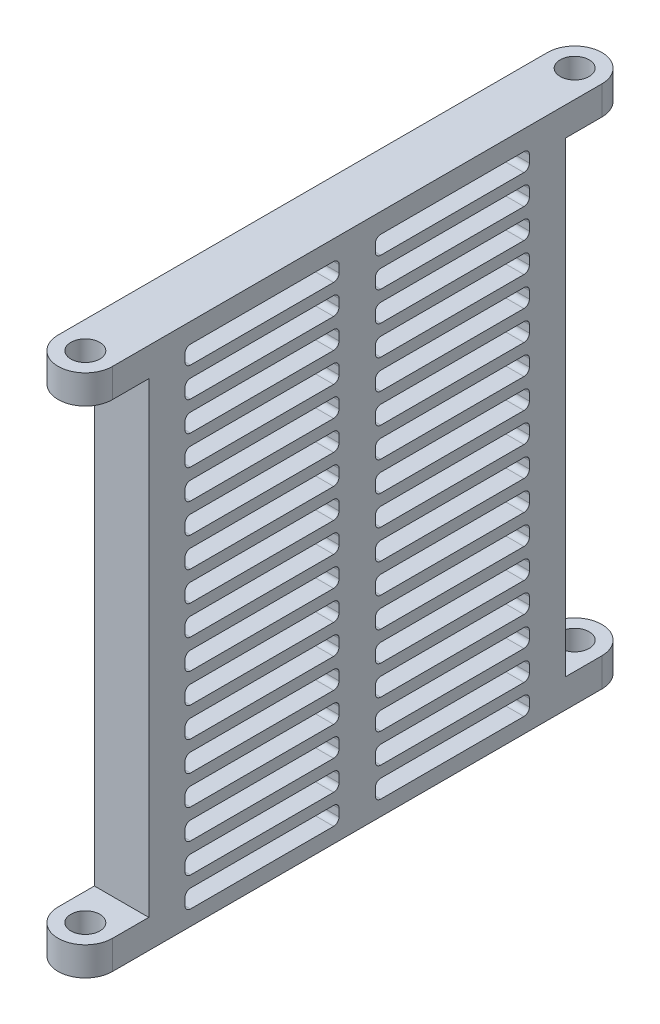
SolidWorks part; units mm, degrees
ref_plane "Front Plane" through (0, 0, 0) normal (0, 0, 1) x (1, 0, 0)
ref_plane "Top Plane" through (0, 0, 0) normal (0, 1, 0) x (1, 0, 0)
ref_plane "Right Plane" through (0, 0, 0) normal (1, 0, 0) x (0, 0, -1)
sketch "Sketch2" plane through (0, 0, 0) normal (0, 1, 0) x (1, 0, 0)
  line L0 (-3, 0) -> (-3, -54)
  line L1 (3, -54) -> (3, 0)
  arc A0 (3, 0) -> (-3, 0) centre (0, 0) ccw
  arc A1 (-3, -54) -> (3, -54) centre (0, -54) ccw
  circle A2 centre (0, 0) radius 1.6
  circle A3 centre (0, -54) radius 1.6
  dimension "D1" = 3.2
  dimension "D2" = 3
  dimension "D3" = 54
extrude "Boss-Extrude1" add sketch "Sketch2" along normal blind 3.175
sketch "Sketch3" plane through (0, 3.175, 0) normal (0, 1, 0) x (1, 0, 0)
  line L0 (-3, 0) -> (-3, -54) construction
  line L1 (-3, -4) -> (3, -4)
  line L2 (-3, -4) -> (-3, -50)
  line L3 (-3, -50) -> (3, -50)
  line L4 (3, -4) -> (3, -50)
  line L5 (3, -54) -> (3, 0) construction
  circle A0 centre (0, -54) radius 1.6 construction
  point P9 (0, -50)
  dimension "D1" = 4
  dimension "D2" = 4
extrude "Boss-Extrude2" add sketch "Sketch3" along normal blind 51.48
ref_plane "Plane1" through (0, 28.915, 0) normal (0, 1, 0) x (1, 0, 0)
mirror "Mirror2" about plane through (0, 28.915, 0) normal (0, 1, 0) of "Boss-Extrude1"
sketch "Sketch4" plane through (3, 0, 0) normal (1, 0, 0) x (0, 0, -1)
  line L0 (-4, 54.655) -> (-50, 54.655) construction
  line L1 (-8.6, 13.4236) -> (-24.4, 13.4236)
  line L2 (-8, 12.8236) -> (-8, 12.0236)
  line L3 (-4, 3.175) -> (-50, 3.175) construction
  line L4 (-8.6, 11.4236) -> (-24.4, 11.4236)
  line L5 (-25, 12.8236) -> (-25, 12.0236)
  line L11 (-27, 57.83) -> (-27, 0) construction
  line L12 (-54, 57.83) -> (0, 57.83) construction
  line L24 (-54, 0) -> (0, 0) construction
  line L25 (-4, 54.655) -> (-4, 3.175) construction
  line L30 (-8.6, 55.655) -> (-24.4, 55.655)
  line L39 (-8, 55.055) -> (-8, 54.255)
  line L40 (-8.6, 53.655) -> (-24.4, 53.655)
  line L41 (-25, 55.055) -> (-25, 54.255)
  line L46 (-8, 55.655) -> (-25, 53.655) construction
  line L47 (-8, 53.655) -> (-25, 55.655) construction
  line L64 (-8.6, 52.4064) -> (-24.4, 52.4064)
  line L69 (-8, 51.8064) -> (-8, 51.0064)
  line L70 (-8.6, 50.4064) -> (-24.4, 50.4064)
  line L71 (-25, 51.8064) -> (-25, 51.0064)
  line L72 (-4, 51.4064) -> (-50, 51.4064) construction
  line L73 (-8, 52.4064) -> (-25, 50.4064) construction
  line L74 (-8, 50.4064) -> (-25, 52.4064) construction
  line L75 (-8.6, 49.1579) -> (-24.4, 49.1579)
  line L76 (-8, 48.5579) -> (-8, 47.7579)
  line L77 (-8.6, 47.1579) -> (-24.4, 47.1579)
  line L78 (-25, 48.5579) -> (-25, 47.7579)
  line L79 (-4, 48.1579) -> (-50, 48.1579) construction
  line L132 (-8, 49.1579) -> (-25, 47.1579) construction
  line L133 (-8, 47.1579) -> (-25, 49.1579) construction
  line L134 (-8.6, 45.9093) -> (-24.4, 45.9093)
  line L135 (-8, 45.3093) -> (-8, 44.5093)
  line L136 (-8.6, 43.9093) -> (-24.4, 43.9093)
  line L137 (-25, 45.3093) -> (-25, 44.5093)
  line L138 (-4, 44.9093) -> (-50, 44.9093) construction
  line L139 (-8, 45.9093) -> (-25, 43.9093) construction
  line L140 (-8, 43.9093) -> (-25, 45.9093) construction
  line L141 (-8.6, 42.6607) -> (-24.4, 42.6607)
  line L142 (-8, 42.0607) -> (-8, 41.2607)
  line L143 (-8.6, 40.6607) -> (-24.4, 40.6607)
  line L144 (-25, 42.0607) -> (-25, 41.2607)
  line L145 (-4, 41.6607) -> (-50, 41.6607) construction
  line L146 (-8, 42.6607) -> (-25, 40.6607) construction
  line L147 (-8, 40.6607) -> (-25, 42.6607) construction
  line L148 (-8.6, 39.4121) -> (-24.4, 39.4121)
  line L149 (-8, 38.8121) -> (-8, 38.0121)
  line L186 (-4, 12.4236) -> (-50, 12.4236) construction
  line L187 (-8, 13.4236) -> (-25, 11.4236) construction
  line L188 (-8, 11.4236) -> (-25, 13.4236) construction
  line L189 (-8.6, 10.175) -> (-24.4, 10.175)
  line L190 (-8, 9.575) -> (-8, 8.775)
  line L191 (-8.6, 8.175) -> (-24.4, 8.175)
  line L192 (-25, 9.575) -> (-25, 8.775)
  line L193 (-4, 9.175) -> (-50, 9.175) construction
  line L194 (-8, 10.175) -> (-25, 8.175) construction
  line L195 (-8, 8.175) -> (-25, 10.175) construction
  line L196 (-46, 1.6779) -> (-29, 3.6779) construction
  line L197 (-46, 3.6779) -> (-29, 1.6779) construction
  line L198 (-46, 4.9264) -> (-29, 6.9264) construction
  line L199 (-46, 6.9264) -> (-29, 4.9264) construction
  line L200 (-46, 14.6721) -> (-29, 16.6721) construction
  line L201 (-8.6, 37.4121) -> (-24.4, 37.4121)
  line L202 (-25, 38.8121) -> (-25, 38.0121)
  line L203 (-4, 38.4121) -> (-50, 38.4121) construction
  line L204 (-8, 39.4121) -> (-25, 37.4121) construction
  line L205 (-8, 37.4121) -> (-25, 39.4121) construction
  line L206 (-8.6, 36.1636) -> (-24.4, 36.1636)
  line L207 (-8, 35.5636) -> (-8, 34.7636)
  line L208 (-8.6, 34.1636) -> (-24.4, 34.1636)
  line L209 (-25, 35.5636) -> (-25, 34.7636)
  line L210 (-4, 35.1636) -> (-50, 35.1636) construction
  line L211 (-8, 36.1636) -> (-25, 34.1636) construction
  line L212 (-8, 34.1636) -> (-25, 36.1636) construction
  line L213 (-8.6, 32.915) -> (-24.4, 32.915)
  line L214 (-8, 32.315) -> (-8, 31.515)
  line L215 (-8.6, 30.915) -> (-24.4, 30.915)
  line L216 (-25, 32.315) -> (-25, 31.515)
  line L217 (-4, 31.915) -> (-50, 31.915) construction
  line L218 (-8, 32.915) -> (-25, 30.915) construction
  line L219 (-8, 30.915) -> (-25, 32.915) construction
  line L220 (-8.6, 29.6664) -> (-24.4, 29.6664)
  line L221 (-8, 29.0664) -> (-8, 28.2664)
  line L222 (-8.6, 27.6664) -> (-24.4, 27.6664)
  line L223 (-25, 29.0664) -> (-25, 28.2664)
  line L224 (-4, 28.6664) -> (-50, 28.6664) construction
  line L225 (-8, 29.6664) -> (-25, 27.6664) construction
  line L226 (-8, 27.6664) -> (-25, 29.6664) construction
  line L227 (-8.6, 26.4179) -> (-24.4, 26.4179)
  line L228 (-8, 25.8179) -> (-8, 25.0179)
  line L229 (-8.6, 24.4179) -> (-24.4, 24.4179)
  line L230 (-25, 25.8179) -> (-25, 25.0179)
  line L231 (-4, 25.4179) -> (-50, 25.4179) construction
  line L232 (-8, 26.4179) -> (-25, 24.4179) construction
  line L233 (-8, 24.4179) -> (-25, 26.4179) construction
  line L234 (-8.6, 23.1693) -> (-24.4, 23.1693)
  line L235 (-8, 22.5693) -> (-8, 21.7693)
  line L236 (-8.6, 21.1693) -> (-24.4, 21.1693)
  line L237 (-25, 22.5693) -> (-25, 21.7693)
  line L238 (-4, 22.1693) -> (-50, 22.1693) construction
  line L239 (-8, 23.1693) -> (-25, 21.1693) construction
  line L240 (-8, 21.1693) -> (-25, 23.1693) construction
  line L241 (-8.6, 19.9207) -> (-24.4, 19.9207)
  line L242 (-8, 19.3207) -> (-8, 18.5207)
  line L243 (-8.6, 17.9207) -> (-24.4, 17.9207)
  line L244 (-25, 19.3207) -> (-25, 18.5207)
  line L245 (-4, 18.9207) -> (-50, 18.9207) construction
  line L246 (-8, 19.9207) -> (-25, 17.9207) construction
  line L247 (-8, 17.9207) -> (-25, 19.9207) construction
  line L248 (-8.6, 16.6721) -> (-24.4, 16.6721)
  line L249 (-8, 16.0721) -> (-8, 15.2721)
  line L250 (-8.6, 14.6721) -> (-24.4, 14.6721)
  line L251 (-25, 16.0721) -> (-25, 15.2721)
  line L252 (-4, 15.6721) -> (-50, 15.6721) construction
  line L253 (-8, 16.6721) -> (-25, 14.6721) construction
  line L254 (-8, 14.6721) -> (-25, 16.6721) construction
  line L255 (-46, 16.6721) -> (-29, 14.6721) construction
  line L256 (-46, 17.9207) -> (-29, 19.9207) construction
  line L257 (-46, 19.9207) -> (-29, 17.9207) construction
  line L258 (-46, 21.1693) -> (-29, 23.1693) construction
  line L259 (-46, 23.1693) -> (-29, 21.1693) construction
  line L260 (-46, 24.4179) -> (-29, 26.4179) construction
  line L261 (-46, 26.4179) -> (-29, 24.4179) construction
  line L262 (-46, 27.6664) -> (-29, 29.6664) construction
  line L263 (-46, 29.6664) -> (-29, 27.6664) construction
  line L264 (-46, 30.915) -> (-29, 32.915) construction
  line L265 (-46, 32.915) -> (-29, 30.915) construction
  line L266 (-46, 34.1636) -> (-29, 36.1636) construction
  line L267 (-46, 36.1636) -> (-29, 34.1636) construction
  line L268 (-46, 37.4121) -> (-29, 39.4121) construction
  line L269 (-46, 39.4121) -> (-29, 37.4121) construction
  line L270 (-46, 8.175) -> (-29, 10.175) construction
  line L271 (-46, 10.175) -> (-29, 8.175) construction
  line L272 (-46, 11.4236) -> (-29, 13.4236) construction
  line L273 (-46, 13.4236) -> (-29, 11.4236) construction
  line L274 (-46, 40.6607) -> (-29, 42.6607) construction
  line L275 (-46, 42.6607) -> (-29, 40.6607) construction
  line L276 (-46, 43.9093) -> (-29, 45.9093) construction
  line L277 (-46, 45.9093) -> (-29, 43.9093) construction
  line L278 (-46, 47.1579) -> (-29, 49.1579) construction
  line L279 (-46, 49.1579) -> (-29, 47.1579) construction
  line L392 (-8.6, 6.9264) -> (-24.4, 6.9264)
  line L393 (-8, 6.3264) -> (-8, 5.5264)
  line L394 (-8.6, 4.9264) -> (-24.4, 4.9264)
  line L395 (-25, 6.3264) -> (-25, 5.5264)
  line L396 (-4, 5.9264) -> (-50, 5.9264) construction
  line L397 (-8, 6.9264) -> (-25, 4.9264) construction
  line L398 (-8, 4.9264) -> (-25, 6.9264) construction
  line L399 (-8.6, 3.6779) -> (-24.4, 3.6779)
  line L400 (-8, 3.0779) -> (-8, 2.2779)
  line L401 (-8.6, 1.6779) -> (-24.4, 1.6779)
  line L402 (-25, 3.0779) -> (-25, 2.2779)
  line L403 (-4, 2.6779) -> (-50, 2.6779) construction
  line L404 (-8, 3.6779) -> (-25, 1.6779) construction
  line L405 (-8, 1.6779) -> (-25, 3.6779) construction
  line L406 (-46, 50.4064) -> (-29, 52.4064) construction
  line L407 (-46, 52.4064) -> (-29, 50.4064) construction
  line L408 (-46, 53.655) -> (-29, 55.655) construction
  line L409 (-46, 55.655) -> (-29, 53.655) construction
  line L410 (-29, 3.0779) -> (-29, 2.2779)
  line L411 (-45.4, 1.6779) -> (-29.6, 1.6779)
  line L412 (-46, 3.0779) -> (-46, 2.2779)
  line L413 (-45.4, 3.6779) -> (-29.6, 3.6779)
  line L414 (-29, 6.3264) -> (-29, 5.5264)
  line L415 (-45.4, 4.9264) -> (-29.6, 4.9264)
  line L416 (-46, 6.3264) -> (-46, 5.5264)
  line L417 (-45.4, 6.9264) -> (-29.6, 6.9264)
  line L418 (-29, 16.0721) -> (-29, 15.2721)
  line L419 (-45.4, 14.6721) -> (-29.6, 14.6721)
  line L420 (-46, 16.0721) -> (-46, 15.2721)
  line L421 (-45.4, 16.6721) -> (-29.6, 16.6721)
  line L422 (-29, 19.3207) -> (-29, 18.5207)
  line L423 (-45.4, 17.9207) -> (-29.6, 17.9207)
  line L424 (-46, 19.3207) -> (-46, 18.5207)
  line L425 (-45.4, 19.9207) -> (-29.6, 19.9207)
  line L426 (-29, 22.5693) -> (-29, 21.7693)
  line L427 (-45.4, 21.1693) -> (-29.6, 21.1693)
  line L428 (-46, 22.5693) -> (-46, 21.7693)
  line L429 (-45.4, 23.1693) -> (-29.6, 23.1693)
  line L430 (-29, 25.8179) -> (-29, 25.0179)
  line L431 (-45.4, 24.4179) -> (-29.6, 24.4179)
  line L432 (-46, 25.8179) -> (-46, 25.0179)
  line L433 (-45.4, 26.4179) -> (-29.6, 26.4179)
  line L434 (-29, 29.0664) -> (-29, 28.2664)
  line L435 (-45.4, 27.6664) -> (-29.6, 27.6664)
  line L436 (-46, 29.0664) -> (-46, 28.2664)
  line L437 (-45.4, 29.6664) -> (-29.6, 29.6664)
  line L438 (-29, 32.315) -> (-29, 31.515)
  line L439 (-45.4, 30.915) -> (-29.6, 30.915)
  line L440 (-46, 32.315) -> (-46, 31.515)
  line L441 (-45.4, 32.915) -> (-29.6, 32.915)
  line L442 (-29, 35.5636) -> (-29, 34.7636)
  line L443 (-45.4, 34.1636) -> (-29.6, 34.1636)
  line L444 (-46, 35.5636) -> (-46, 34.7636)
  line L445 (-45.4, 36.1636) -> (-29.6, 36.1636)
  line L446 (-29, 38.8121) -> (-29, 38.0121)
  line L447 (-45.4, 37.4121) -> (-29.6, 37.4121)
  line L448 (-29, 9.575) -> (-29, 8.775)
  line L449 (-45.4, 8.175) -> (-29.6, 8.175)
  line L450 (-46, 9.575) -> (-46, 8.775)
  line L451 (-45.4, 10.175) -> (-29.6, 10.175)
  line L452 (-46, 38.8121) -> (-46, 38.0121)
  line L453 (-45.4, 39.4121) -> (-29.6, 39.4121)
  line L454 (-29, 42.0607) -> (-29, 41.2607)
  line L455 (-45.4, 40.6607) -> (-29.6, 40.6607)
  line L456 (-46, 42.0607) -> (-46, 41.2607)
  line L457 (-45.4, 42.6607) -> (-29.6, 42.6607)
  line L458 (-29, 45.3093) -> (-29, 44.5093)
  line L459 (-45.4, 43.9093) -> (-29.6, 43.9093)
  line L460 (-46, 45.3093) -> (-46, 44.5093)
  line L461 (-45.4, 45.9093) -> (-29.6, 45.9093)
  line L462 (-29, 48.5579) -> (-29, 47.7579)
  line L463 (-45.4, 47.1579) -> (-29.6, 47.1579)
  line L464 (-46, 48.5579) -> (-46, 47.7579)
  line L465 (-45.4, 49.1579) -> (-29.6, 49.1579)
  line L466 (-29, 51.8064) -> (-29, 51.0064)
  line L467 (-45.4, 50.4064) -> (-29.6, 50.4064)
  line L468 (-46, 51.8064) -> (-46, 51.0064)
  line L469 (-45.4, 52.4064) -> (-29.6, 52.4064)
  line L470 (-29, 55.055) -> (-29, 54.255)
  line L471 (-45.4, 53.655) -> (-29.6, 53.655)
  line L472 (-46, 55.055) -> (-46, 54.255)
  line L473 (-45.4, 55.655) -> (-29.6, 55.655)
  line L474 (-29, 12.8236) -> (-29, 12.0236)
  line L475 (-45.4, 11.4236) -> (-29.6, 11.4236)
  line L476 (-46, 12.8236) -> (-46, 12.0236)
  line L477 (-45.4, 13.4236) -> (-29.6, 13.4236)
  arc A72 (-24.4, 13.4236) -> (-25, 12.8236) centre (-24.4, 12.8236) ccw
  arc A73 (-24.4, 11.4236) -> (-25, 12.0236) centre (-24.4, 12.0236) cw
  arc A74 (-8.6, 13.4236) -> (-8, 12.8236) centre (-8.6, 12.8236) cw
  arc A75 (-8, 12.0236) -> (-8.6, 11.4236) centre (-8.6, 12.0236) cw
  arc A76 (-24.4, 55.655) -> (-25, 55.055) centre (-24.4, 55.055) ccw
  arc A77 (-24.4, 53.655) -> (-25, 54.255) centre (-24.4, 54.255) cw
  arc A78 (-8.6, 55.655) -> (-8, 55.055) centre (-8.6, 55.055) cw
  arc A79 (-8, 54.255) -> (-8.6, 53.655) centre (-8.6, 54.255) cw
  arc A80 (-24.4, 52.4064) -> (-25, 51.8064) centre (-24.4, 51.8064) ccw
  arc A81 (-24.4, 50.4064) -> (-25, 51.0064) centre (-24.4, 51.0064) cw
  arc A82 (-8.6, 52.4064) -> (-8, 51.8064) centre (-8.6, 51.8064) cw
  arc A83 (-8, 51.0064) -> (-8.6, 50.4064) centre (-8.6, 51.0064) cw
  arc A84 (-24.4, 49.1579) -> (-25, 48.5579) centre (-24.4, 48.5579) ccw
  arc A85 (-24.4, 47.1579) -> (-25, 47.7579) centre (-24.4, 47.7579) cw
  arc A86 (-8.6, 49.1579) -> (-8, 48.5579) centre (-8.6, 48.5579) cw
  arc A87 (-8, 47.7579) -> (-8.6, 47.1579) centre (-8.6, 47.7579) cw
  arc A88 (-24.4, 45.9093) -> (-25, 45.3093) centre (-24.4, 45.3093) ccw
  arc A89 (-24.4, 43.9093) -> (-25, 44.5093) centre (-24.4, 44.5093) cw
  arc A90 (-8.6, 45.9093) -> (-8, 45.3093) centre (-8.6, 45.3093) cw
  arc A91 (-8, 44.5093) -> (-8.6, 43.9093) centre (-8.6, 44.5093) cw
  arc A92 (-24.4, 42.6607) -> (-25, 42.0607) centre (-24.4, 42.0607) ccw
  arc A93 (-24.4, 40.6607) -> (-25, 41.2607) centre (-24.4, 41.2607) cw
  arc A94 (-8.6, 42.6607) -> (-8, 42.0607) centre (-8.6, 42.0607) cw
  arc A95 (-8, 41.2607) -> (-8.6, 40.6607) centre (-8.6, 41.2607) cw
  arc A96 (-24.4, 39.4121) -> (-25, 38.8121) centre (-24.4, 38.8121) ccw
  arc A97 (-24.4, 37.4121) -> (-25, 38.0121) centre (-24.4, 38.0121) cw
  arc A98 (-8.6, 39.4121) -> (-8, 38.8121) centre (-8.6, 38.8121) cw
  arc A99 (-8, 38.0121) -> (-8.6, 37.4121) centre (-8.6, 38.0121) cw
  arc A100 (-24.4, 36.1636) -> (-25, 35.5636) centre (-24.4, 35.5636) ccw
  arc A101 (-24.4, 34.1636) -> (-25, 34.7636) centre (-24.4, 34.7636) cw
  arc A102 (-8.6, 36.1636) -> (-8, 35.5636) centre (-8.6, 35.5636) cw
  arc A103 (-8, 34.7636) -> (-8.6, 34.1636) centre (-8.6, 34.7636) cw
  arc A104 (-24.4, 32.915) -> (-25, 32.315) centre (-24.4, 32.315) ccw
  arc A105 (-24.4, 30.915) -> (-25, 31.515) centre (-24.4, 31.515) cw
  arc A106 (-8.6, 32.915) -> (-8, 32.315) centre (-8.6, 32.315) cw
  arc A107 (-8, 31.515) -> (-8.6, 30.915) centre (-8.6, 31.515) cw
  arc A108 (-24.4, 29.6664) -> (-25, 29.0664) centre (-24.4, 29.0664) ccw
  arc A109 (-24.4, 27.6664) -> (-25, 28.2664) centre (-24.4, 28.2664) cw
  arc A110 (-8.6, 29.6664) -> (-8, 29.0664) centre (-8.6, 29.0664) cw
  arc A111 (-8, 28.2664) -> (-8.6, 27.6664) centre (-8.6, 28.2664) cw
  arc A112 (-24.4, 26.4179) -> (-25, 25.8179) centre (-24.4, 25.8179) ccw
  arc A113 (-24.4, 24.4179) -> (-25, 25.0179) centre (-24.4, 25.0179) cw
  arc A114 (-8.6, 26.4179) -> (-8, 25.8179) centre (-8.6, 25.8179) cw
  arc A115 (-8, 25.0179) -> (-8.6, 24.4179) centre (-8.6, 25.0179) cw
  arc A116 (-24.4, 23.1693) -> (-25, 22.5693) centre (-24.4, 22.5693) ccw
  arc A117 (-24.4, 21.1693) -> (-25, 21.7693) centre (-24.4, 21.7693) cw
  arc A118 (-8.6, 23.1693) -> (-8, 22.5693) centre (-8.6, 22.5693) cw
  arc A119 (-8, 21.7693) -> (-8.6, 21.1693) centre (-8.6, 21.7693) cw
  arc A120 (-24.4, 19.9207) -> (-25, 19.3207) centre (-24.4, 19.3207) ccw
  arc A121 (-24.4, 17.9207) -> (-25, 18.5207) centre (-24.4, 18.5207) cw
  arc A122 (-8.6, 19.9207) -> (-8, 19.3207) centre (-8.6, 19.3207) cw
  arc A123 (-8, 18.5207) -> (-8.6, 17.9207) centre (-8.6, 18.5207) cw
  arc A124 (-24.4, 16.6721) -> (-25, 16.0721) centre (-24.4, 16.0721) ccw
  arc A125 (-24.4, 14.6721) -> (-25, 15.2721) centre (-24.4, 15.2721) cw
  arc A126 (-8.6, 16.6721) -> (-8, 16.0721) centre (-8.6, 16.0721) cw
  arc A127 (-8, 15.2721) -> (-8.6, 14.6721) centre (-8.6, 15.2721) cw
  arc A180 (-24.4, 10.175) -> (-25, 9.575) centre (-24.4, 9.575) ccw
  arc A181 (-24.4, 8.175) -> (-25, 8.775) centre (-24.4, 8.775) cw
  arc A182 (-8.6, 10.175) -> (-8, 9.575) centre (-8.6, 9.575) cw
  arc A183 (-8, 8.775) -> (-8.6, 8.175) centre (-8.6, 8.775) cw
  arc A244 (-24.4, 6.9264) -> (-25, 6.3264) centre (-24.4, 6.3264) ccw
  arc A245 (-24.4, 4.9264) -> (-25, 5.5264) centre (-24.4, 5.5264) cw
  arc A246 (-8.6, 6.9264) -> (-8, 6.3264) centre (-8.6, 6.3264) cw
  arc A247 (-8, 5.5264) -> (-8.6, 4.9264) centre (-8.6, 5.5264) cw
  arc A248 (-24.4, 3.6779) -> (-25, 3.0779) centre (-24.4, 3.0779) ccw
  arc A249 (-24.4, 1.6779) -> (-25, 2.2779) centre (-24.4, 2.2779) cw
  arc A250 (-8.6, 3.6779) -> (-8, 3.0779) centre (-8.6, 3.0779) cw
  arc A251 (-8, 2.2779) -> (-8.6, 1.6779) centre (-8.6, 2.2779) cw
  arc A252 (-46, 2.2779) -> (-45.4, 1.6779) centre (-45.4, 2.2779) ccw
  arc A253 (-45.4, 3.6779) -> (-46, 3.0779) centre (-45.4, 3.0779) ccw
  arc A254 (-29.6, 1.6779) -> (-29, 2.2779) centre (-29.6, 2.2779) ccw
  arc A255 (-29.6, 3.6779) -> (-29, 3.0779) centre (-29.6, 3.0779) cw
  arc A256 (-46, 5.5264) -> (-45.4, 4.9264) centre (-45.4, 5.5264) ccw
  arc A257 (-45.4, 6.9264) -> (-46, 6.3264) centre (-45.4, 6.3264) ccw
  arc A258 (-29.6, 4.9264) -> (-29, 5.5264) centre (-29.6, 5.5264) ccw
  arc A259 (-29.6, 6.9264) -> (-29, 6.3264) centre (-29.6, 6.3264) cw
  arc A260 (-46, 8.775) -> (-45.4, 8.175) centre (-45.4, 8.775) ccw
  arc A261 (-45.4, 10.175) -> (-46, 9.575) centre (-45.4, 9.575) ccw
  arc A262 (-29.6, 8.175) -> (-29, 8.775) centre (-29.6, 8.775) ccw
  arc A263 (-29.6, 10.175) -> (-29, 9.575) centre (-29.6, 9.575) cw
  arc A264 (-46, 15.2721) -> (-45.4, 14.6721) centre (-45.4, 15.2721) ccw
  arc A265 (-45.4, 16.6721) -> (-46, 16.0721) centre (-45.4, 16.0721) ccw
  arc A266 (-29.6, 14.6721) -> (-29, 15.2721) centre (-29.6, 15.2721) ccw
  arc A267 (-29.6, 16.6721) -> (-29, 16.0721) centre (-29.6, 16.0721) cw
  arc A268 (-46, 18.5207) -> (-45.4, 17.9207) centre (-45.4, 18.5207) ccw
  arc A269 (-45.4, 19.9207) -> (-46, 19.3207) centre (-45.4, 19.3207) ccw
  arc A270 (-29.6, 17.9207) -> (-29, 18.5207) centre (-29.6, 18.5207) ccw
  arc A271 (-29.6, 19.9207) -> (-29, 19.3207) centre (-29.6, 19.3207) cw
  arc A272 (-46, 21.7693) -> (-45.4, 21.1693) centre (-45.4, 21.7693) ccw
  arc A273 (-45.4, 23.1693) -> (-46, 22.5693) centre (-45.4, 22.5693) ccw
  arc A274 (-29.6, 21.1693) -> (-29, 21.7693) centre (-29.6, 21.7693) ccw
  arc A275 (-29.6, 23.1693) -> (-29, 22.5693) centre (-29.6, 22.5693) cw
  arc A276 (-46, 25.0179) -> (-45.4, 24.4179) centre (-45.4, 25.0179) ccw
  arc A277 (-45.4, 26.4179) -> (-46, 25.8179) centre (-45.4, 25.8179) ccw
  arc A278 (-29.6, 24.4179) -> (-29, 25.0179) centre (-29.6, 25.0179) ccw
  arc A279 (-29.6, 26.4179) -> (-29, 25.8179) centre (-29.6, 25.8179) cw
  arc A280 (-46, 28.2664) -> (-45.4, 27.6664) centre (-45.4, 28.2664) ccw
  arc A281 (-45.4, 29.6664) -> (-46, 29.0664) centre (-45.4, 29.0664) ccw
  arc A282 (-29.6, 27.6664) -> (-29, 28.2664) centre (-29.6, 28.2664) ccw
  arc A283 (-29.6, 29.6664) -> (-29, 29.0664) centre (-29.6, 29.0664) cw
  arc A284 (-46, 31.515) -> (-45.4, 30.915) centre (-45.4, 31.515) ccw
  arc A285 (-45.4, 32.915) -> (-46, 32.315) centre (-45.4, 32.315) ccw
  arc A286 (-29.6, 30.915) -> (-29, 31.515) centre (-29.6, 31.515) ccw
  arc A287 (-29.6, 32.915) -> (-29, 32.315) centre (-29.6, 32.315) cw
  arc A288 (-46, 34.7636) -> (-45.4, 34.1636) centre (-45.4, 34.7636) ccw
  arc A289 (-45.4, 36.1636) -> (-46, 35.5636) centre (-45.4, 35.5636) ccw
  arc A290 (-29.6, 34.1636) -> (-29, 34.7636) centre (-29.6, 34.7636) ccw
  arc A291 (-29.6, 36.1636) -> (-29, 35.5636) centre (-29.6, 35.5636) cw
  arc A292 (-46, 38.0121) -> (-45.4, 37.4121) centre (-45.4, 38.0121) ccw
  arc A293 (-45.4, 39.4121) -> (-46, 38.8121) centre (-45.4, 38.8121) ccw
  arc A294 (-29.6, 37.4121) -> (-29, 38.0121) centre (-29.6, 38.0121) ccw
  arc A295 (-29.6, 39.4121) -> (-29, 38.8121) centre (-29.6, 38.8121) cw
  arc A296 (-46, 41.2607) -> (-45.4, 40.6607) centre (-45.4, 41.2607) ccw
  arc A297 (-45.4, 42.6607) -> (-46, 42.0607) centre (-45.4, 42.0607) ccw
  arc A298 (-29.6, 40.6607) -> (-29, 41.2607) centre (-29.6, 41.2607) ccw
  arc A299 (-29.6, 42.6607) -> (-29, 42.0607) centre (-29.6, 42.0607) cw
  arc A300 (-46, 44.5093) -> (-45.4, 43.9093) centre (-45.4, 44.5093) ccw
  arc A301 (-45.4, 45.9093) -> (-46, 45.3093) centre (-45.4, 45.3093) ccw
  arc A302 (-29.6, 43.9093) -> (-29, 44.5093) centre (-29.6, 44.5093) ccw
  arc A303 (-29.6, 45.9093) -> (-29, 45.3093) centre (-29.6, 45.3093) cw
  arc A304 (-46, 47.7579) -> (-45.4, 47.1579) centre (-45.4, 47.7579) ccw
  arc A305 (-45.4, 49.1579) -> (-46, 48.5579) centre (-45.4, 48.5579) ccw
  arc A306 (-29.6, 47.1579) -> (-29, 47.7579) centre (-29.6, 47.7579) ccw
  arc A307 (-29.6, 49.1579) -> (-29, 48.5579) centre (-29.6, 48.5579) cw
  arc A308 (-46, 51.0064) -> (-45.4, 50.4064) centre (-45.4, 51.0064) ccw
  arc A309 (-45.4, 52.4064) -> (-46, 51.8064) centre (-45.4, 51.8064) ccw
  arc A310 (-29.6, 50.4064) -> (-29, 51.0064) centre (-29.6, 51.0064) ccw
  arc A311 (-29.6, 52.4064) -> (-29, 51.8064) centre (-29.6, 51.8064) cw
  arc A312 (-46, 54.255) -> (-45.4, 53.655) centre (-45.4, 54.255) ccw
  arc A313 (-45.4, 55.655) -> (-46, 55.055) centre (-45.4, 55.055) ccw
  arc A314 (-29.6, 53.655) -> (-29, 54.255) centre (-29.6, 54.255) ccw
  arc A315 (-29.6, 55.655) -> (-29, 55.055) centre (-29.6, 55.055) cw
  arc A316 (-46, 12.0236) -> (-45.4, 11.4236) centre (-45.4, 12.0236) ccw
  arc A317 (-45.4, 13.4236) -> (-46, 12.8236) centre (-45.4, 12.8236) ccw
  arc A318 (-29.6, 11.4236) -> (-29, 12.0236) centre (-29.6, 12.0236) ccw
  arc A319 (-29.6, 13.4236) -> (-29, 12.8236) centre (-29.6, 12.8236) cw
  point P10 (-16.5, 54.655)
  point P13 (-14.25, 34.325)
  point P14 (-14.25, 31.825)
  point P15 (-14.25, 29.325)
  point P16 (-14.25, 26.825)
  point P36 (-16.5, 51.4064)
  point P55 (-16.5, 48.1579)
  point P74 (-16.5, 44.9093)
  point P93 (-16.5, 41.6607)
  point P112 (-16.5, 38.4121)
  point P131 (-16.5, 35.1636)
  point P150 (-16.5, 31.915)
  point P169 (-16.5, 28.6664)
  point P188 (-16.5, 25.4179)
  point P207 (-16.5, 22.1693)
  point P226 (-16.5, 18.9207)
  point P245 (-16.5, 15.6721)
  point P328 (-16.5, 12.4236)
  point P347 (-16.5, 9.175)
  point P560 (-16.5, 5.9264)
  point P579 (-16.5, 2.6779)
  point P613 (-37.5, 2.6779)
  point P614 (-37.5, 5.9264)
  point P615 (-37.5, 9.175)
  point P616 (-37.5, 12.4236)
  point P617 (-37.5, 15.6721)
  point P618 (-37.5, 18.9207)
  point P619 (-37.5, 22.1693)
  point P620 (-37.5, 25.4179)
  point P621 (-37.5, 28.6664)
  point P622 (-37.5, 31.915)
  point P623 (-37.5, 35.1636)
  point P624 (-37.5, 38.4121)
  point P625 (-37.5, 41.6607)
  point P626 (-37.5, 44.9093)
  point P627 (-37.5, 48.1579)
  point P628 (-37.5, 51.4064)
  point P629 (-37.5, 54.655)
  dimension "D6" = 1.2486
  dimension "D4" = 0.6
  dimension "D1" = 2
  dimension "D2" = 4
  dimension "D3" = 2
  dimension "D5" = 17
extrude "Cut-Extrude1" cut sketch "Sketch4" against normal through all
equation "\"D2@Sketch3\"=\"D1@Sketch3\""
